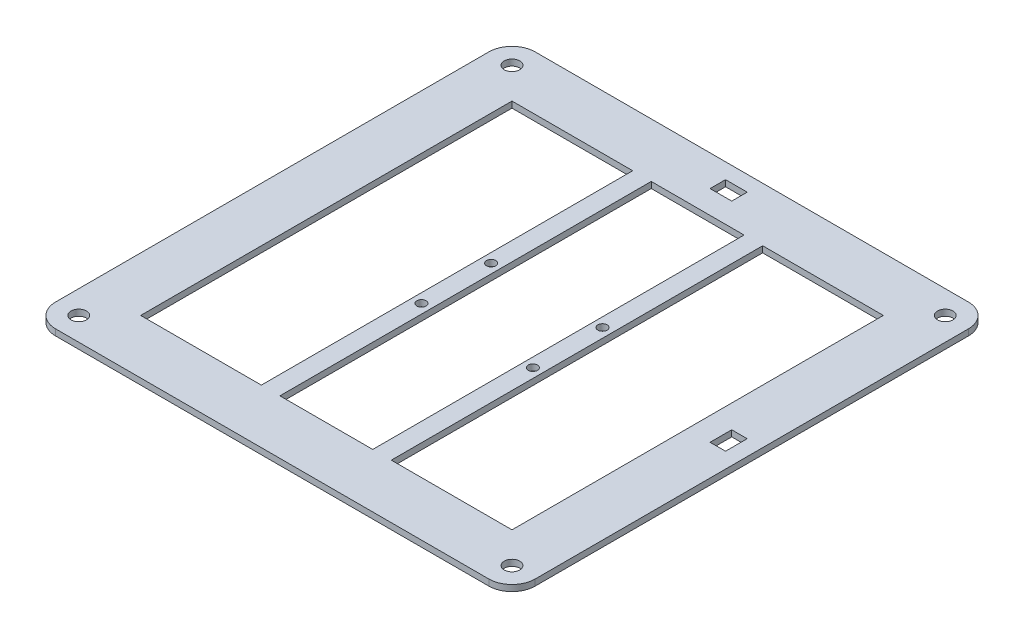
SolidWorks part; units mm, degrees
ref_plane "Alzado" through (0, 0, 0) normal (0, 0, 1) x (1, 0, 0)
ref_plane "Planta" through (0, 0, 0) normal (0, 1, 0) x (1, 0, 0)
ref_plane "Vista lateral" through (0, 0, 0) normal (1, 0, 0) x (0, 0, -1)
sketch "Croquis1" plane through (0, 0, 0) normal (0, 1, 0) x (1, 0, 0)
  line L0 (-10, -10) -> (-10, 150)
  line L1 (0, 0) -> (140, 0) construction
  line L2 (0, 0) -> (0, 140) construction
  line L3 (0, 140) -> (140, 140) construction
  line L4 (140, 0) -> (140, 140) construction
  line L5 (-10, 150) -> (150, 150)
  line L6 (150, -10) -> (150, 150)
  line L7 (-10, -10) -> (150, -10)
  line L8 (10, 10) -> (10, 130)
  line L9 (10, 130) -> (49, 130)
  line L10 (130, 10) -> (130, 130)
  line L11 (10, 10) -> (49, 10)
  line L12 (10, 70) -> (130, 70) construction
  line L13 (52, 70) -> (52, 81.25) construction
  line L14 (52, 70) -> (52, 58.75) construction
  line L15 (70, 70) -> (70, 160) construction
  line L16 (49, 147.7957) -> (55, 147.7957) construction
  line L18 (49, 130) -> (49, 10)
  line L20 (55, 130) -> (55, 10)
  line L21 (52, 147.7957) -> (52, 81.25) construction
  line L22 (55, 130) -> (85, 130)
  line L23 (55, 10) -> (85, 10)
  line L24 (10, 130) -> (130, 130) construction
  line L25 (85, 130) -> (85, 10)
  line L26 (10, 10) -> (130, 10) construction
  line L27 (91, 130) -> (91, 10)
  line L28 (91, 130) -> (130, 130)
  line L29 (91, 10) -> (130, 10)
  line L31 (137.5, 66.5) -> (142.5, 66.5)
  line L32 (137.5, 66.5) -> (137.5, 73.5)
  line L33 (137.5, 73.5) -> (142.5, 73.5)
  line L34 (142.5, 66.5) -> (142.5, 73.5)
  line L35 (137.5, 66.5) -> (142.5, 73.5) construction
  line L36 (137.5, 73.5) -> (142.5, 66.5) construction
  line L37 (66.5, 142.5) -> (73.5, 142.5)
  line L38 (66.5, 142.5) -> (66.5, 137.5)
  line L39 (66.5, 137.5) -> (73.5, 137.5)
  line L40 (73.5, 142.5) -> (73.5, 137.5)
  line L41 (66.5, 142.5) -> (73.5, 137.5) construction
  line L42 (66.5, 137.5) -> (73.5, 142.5) construction
  circle A0 centre (52, 81.25) radius 1.5
  circle A1 centre (52, 58.75) radius 1.5
  circle A2 centre (0, 140) radius 2.5
  circle A3 centre (0, 0) radius 2.5
  circle A4 centre (88, 81.25) radius 1.5
  circle A5 centre (88, 58.75) radius 1.5
  circle A6 centre (140, 0) radius 2.5
  circle A7 centre (140, 140) radius 2.5
  point P41 (140, 70)
  point P46 (70, 140)
  dimension "D4" = 3
  dimension "D8" = 5
  dimension "D1" = 140
  dimension "D2" = 10
  dimension "D5" = 18
  dimension "D6" = 11.25
  dimension "D7" = 6
  dimension "D9" = 5
  dimension "D10" = 7
  dimension "D3" = 10
extrude "Saliente-Extruir1" add sketch "Croquis1" along normal blind 2
sketch "Croquis2" plane through (0, 2, 0) normal (0, 1, 0) x (1, 0, 0)
  line L0 (0, 147.5) -> (140, 147.5)
  line L1 (147.5, 140) -> (147.5, 0)
  line L2 (140, -7.5) -> (0, -7.5)
  line L3 (-7.5, 0) -> (-7.5, 140)
  line L8 (-10, -10) -> (150, -10)
  line L9 (150, -10) -> (150, 150)
  line L10 (150, 150) -> (-10, 150)
  line L11 (-10, 150) -> (-10, -10)
  line L12 (-10, -10) -> (150, -10)
  line L13 (150, -10) -> (150, 150)
  line L14 (150, 150) -> (-10, 150)
  line L15 (-10, 150) -> (-10, -10)
  arc A0 (0, 147.5) -> (-7.5, 140) centre (0, 140) ccw
  arc A1 (147.5, 140) -> (140, 147.5) centre (140, 140) ccw
  arc A2 (140, -7.5) -> (147.5, 0) centre (140, 0) ccw
  arc A3 (-7.5, 0) -> (0, -7.5) centre (0, 0) ccw
  point P20 (-21.3441, 158.6227)
  dimension "D1" = 15
  dimension "D2" = 0
extrude "Cortar-Extruir1" cut sketch "Croquis2" against normal blind 10
